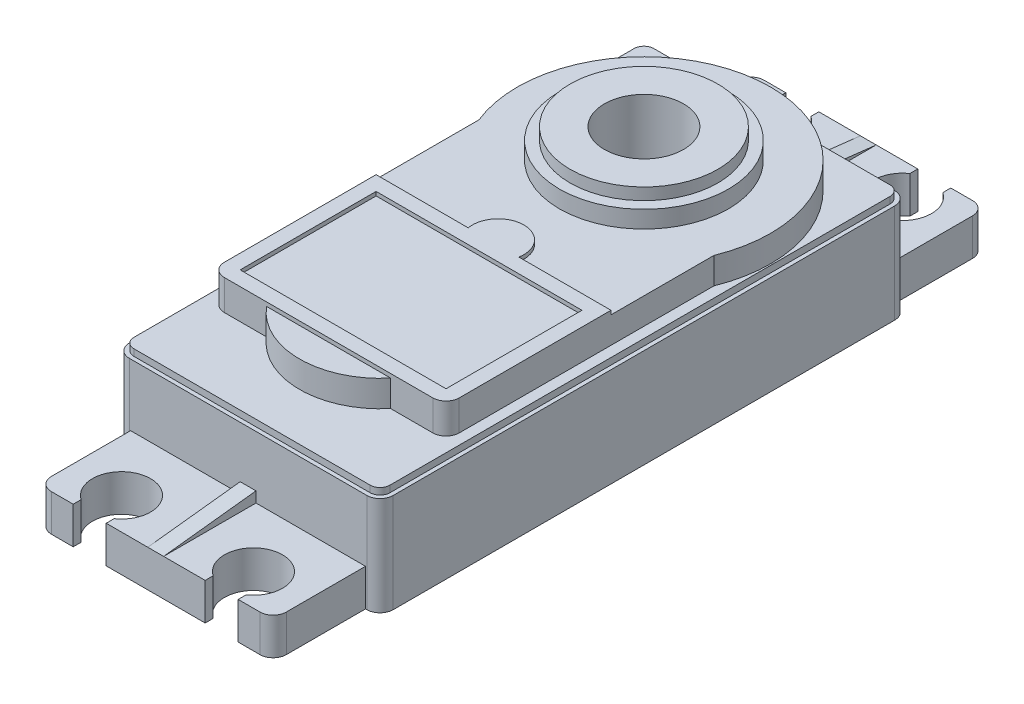
SolidWorks part; units mm, degrees
material "Polyethylene Cross-Linked"
ref_plane "Front Plane" through (0, 0, 0) normal (0, 0, 1) x (1, 0, 0)
ref_plane "Top Plane" through (0, 0, 0) normal (0, 1, 0) x (1, 0, 0)
ref_plane "Right Plane" through (0, 0, 0) normal (1, 0, 0) x (0, 0, -1)
sketch "Sketch6" plane through (0, 0, 0) normal (0, 1, 0) x (1, 0, 0)
  line L0 (-10, 20) -> (10, -20) construction
  line L8 (10, 20) -> (-10, 20)
  line L9 (-10, 20) -> (-10, -20)
  line L10 (-10, -20) -> (10, -20)
  line L11 (10, -20) -> (10, 20)
  dimension "D1" = 40
  dimension "D2" = 20
extrude "Boss-Extrude3" add sketch "Sketch6" along normal blind 8 separate body
sketch "Sketch11" plane through (0, 8, 0) normal (0, 1, 0) x (1, 0, 0)
  line L0 (0, 0) -> (0, 10) construction
  line L1 (0, 10) -> (0, 20) construction
  line L3 (10, 20) -> (-10, 20) construction
  circle A0 centre (0, 10) radius 3
  dimension "D2" = 6
  dimension "D1" = 10
extrude "Cut-Extrude3" cut sketch "Sketch11" against normal up to next
sketch "Sketch12" plane through (0, 0, 20) normal (0, 0, 1) x (1, 0, 0)
  line L1 (-8.9, 2.8) -> (8.9, 2.8)
  line L2 (-8.9, 2.8) -> (-8.9, 0)
  line L3 (-8.9, 0) -> (8.9, 0)
  line L4 (8.9, 2.8) -> (8.9, 0)
  line L6 (-10, 0) -> (10, 0) construction
  dimension "D2" = 2.8
  dimension "D3" = 17.8
extrude "Boss-Extrude4" add sketch "Sketch12" along normal blind 7
sketch "Sketch13" plane through (0, 2.8, 0) normal (0, 1, 0) x (1, 0, 0)
  line L0 (0, -27) -> (0, -20) construction
  line L1 (8.9, -27) -> (-8.9, -27) construction
  line L2 (8.9, -20) -> (-8.9, -20) construction
  line L3 (-6.25, -26.4) -> (-6.25, -27)
  line L4 (-6.25, -27) -> (-3.75, -27)
  line L5 (-3.75, -27) -> (-3.75, -26.4)
  line L6 (-5, -24.5896) -> (-5, -27) construction
  arc A0 (-3.75, -26.4) -> (-6.25, -26.4) centre (-5, -24.5896) ccw
  dimension "D1" = 4.4
  dimension "D2" = 0.6
  dimension "D3" = 5
  dimension "D4" = 2.5
extrude "Cut-Extrude4" cut sketch "Sketch13" against normal through all
mirror "Mirror6" about plane through (0, 0, 0) normal (1, 0, 0) of "Cut-Extrude4"
sketch "Sketch20" plane through (0, 0, 0) normal (0, -1, 0) x (-1, 0, 0)
  line L0 (0, -20) -> (0, -27) construction
  line L1 (-8.9, -20) -> (8.9, -20) construction
  line L3 (3.75, -27) -> (-3.75, -27) construction
  circle A0 centre (0, -25) radius 0.7
  dimension "D1" = 1.4
  dimension "D2" = 5
extrude "Cut-Extrude7" cut sketch "Sketch20" against normal blind 0.5
sketch "Sketch21" plane through (0, 0, 0) normal (1, 0, 0) x (0, 0, -1)
  line L0 (-27, 2.8) -> (-20, 3.6)
  line L1 (-20, 8) -> (-20, 0) construction
  line L2 (-20, 3.6) -> (-20, 2.8)
  line L3 (-20, 2.8) -> (-27, 2.8)
  dimension "D1" = 0.8
extrude "Boss-Extrude8" add sketch "Sketch21" along normal mid plane 1.2
mirror "Mirror7" about plane through (0, 0, 0) normal (0, 0, 1) of "Boss-Extrude8", "Cut-Extrude7", "Mirror6", "Cut-Extrude4", "Boss-Extrude4"
sketch "Sketch28" plane through (0, 8, 0) normal (0, 1, 0) x (1, 0, 0)
  line L0 (-9.7, 19.7) -> (-9.7, -19.7)
  line L1 (-9.7, -19.7) -> (9.7, -19.7)
  line L2 (9.7, -19.7) -> (9.7, 19.7)
  line L3 (9.7, 19.7) -> (-9.7, 19.7)
  line L4 (-10, 20) -> (-10, -20)
  line L5 (-10, -20) -> (10, -20)
  line L6 (10, -20) -> (10, 20)
  line L7 (10, 20) -> (-10, 20)
  line L8 (-10, 20) -> (-10, -20)
  line L9 (-10, -20) -> (10, -20)
  line L10 (10, -20) -> (10, 20)
  line L11 (10, 20) -> (-10, 20)
  dimension "D1" = 0
  dimension "D2" = 0.3
sketch "Sketch16" plane through (0, 8, 0) normal (0, 1, 0) x (1, 0, 0)
  line L0 (-8.9, -13.8986) -> (8.9, -13.8986)
  line L1 (8.9, -13.8986) -> (8.9, 6.4014)
  line L2 (-8.9, -13.8986) -> (-8.9, 6.4014)
  line L3 (0, -13.8986) -> (0, 0) construction
  arc A0 (8.9, 6.4014) -> (-8.9, 6.4014) centre (0, 10) ccw
  circle A1 centre (0, 10) radius 3
  circle A3 centre (0, 10) radius 3 construction
  dimension "D1" = 19.2
  dimension "D3" = 20.3
  dimension "D2" = 17.8
extrude "Boss-Extrude6" add sketch "Sketch16" along normal blind 2
sketch "Sketch23" plane through (0, 8, 0) normal (0, 1, 0) x (1, 0, 0)
  line L1 (-4.7, -13.8986) -> (4.7, -13.8986) construction
  line L2 (-8.9, -13.8986) -> (8.9, -13.8986) construction
  line L3 (0, -13.8986) -> (0, -16.0986) construction
  line L7 (-8.9, -13.8986) -> (8.9, -13.8986)
  line L8 (-8.9, 6.4014) -> (-8.9, -13.8986)
  line L9 (8.9, -13.8986) -> (8.9, 6.4014)
  line L10 (-4.7, -13.8986) -> (4.7, -13.8986)
  arc A0 (-4.7, -13.8986) -> (4.7, -13.8986) centre (0, -9.9782) ccw
  arc A2 (8.9, 6.4014) -> (-8.9, 6.4014) centre (0, 10) ccw
  dimension "D1" = 2.2
  dimension "D2" = 9.4
  dimension "D3" = 0
extrude "Boss-Extrude9" add sketch "Sketch23" along normal up to surface (2 mm away) up to face at (0, 10, 0.449)
sketch "Sketch24" plane through (0, 10, 0) normal (0, 1, 0) x (1, 0, 0)
  circle A0 centre (0, 10) radius 6.4
  circle A1 centre (0, 10) radius 3
  circle A2 centre (0, 10) radius 3 construction
  dimension "D1" = 12.8
extrude "Boss-Extrude10" add sketch "Sketch24" along normal blind 1.3
sketch "Sketch25" plane through (0, 11.3, 0) normal (0, 1, 0) x (1, 0, 0)
  circle A0 centre (0, 10) radius 5.6
  circle A1 centre (0, 10) radius 3
  circle A4 centre (0, 10) radius 3 construction
  dimension "D1" = 11.2
extrude "Boss-Extrude11" add sketch "Sketch25" along normal blind 0.9
sketch "Sketch26" plane through (0, 10, 0) normal (0, 1, 0) x (1, 0, 0)
  line L0 (-8.9, 6.4014) -> (-8.9, -13.8986) construction
  line L1 (-8.9, -1.3986) -> (8.9, -1.3986)
  line L2 (-8.9, -1.3986) -> (-8.9, -13.8986)
  line L3 (-8.9, -13.8986) -> (8.9, -13.8986)
  line L4 (8.9, -1.3986) -> (8.9, -13.8986)
  line L5 (-8.9, -1.3986) -> (8.9, -13.8986) construction
  line L6 (-8.9, -13.8986) -> (8.9, -1.3986) construction
  line L8 (-7.8, -2.4986) -> (7.8, -2.4986)
  line L9 (-7.8, -2.4986) -> (-7.8, -12.7986)
  line L10 (-7.8, -12.7986) -> (7.8, -12.7986)
  line L11 (7.8, -2.4986) -> (7.8, -12.7986)
  line L12 (-7.8, -2.4986) -> (7.8, -12.7986) construction
  line L13 (-7.8, -12.7986) -> (7.8, -2.4986) construction
  point P0 (0, -7.6486)
  point P8 (0, -7.6486)
  dimension "D1" = 12.5
  dimension "D2" = 1.1
  dimension "D3" = 1.1
extrude "Boss-Extrude12" add sketch "Sketch26" along normal blind 0.3
sketch "Sketch27" plane through (0, 10, 0) normal (0, 1, 0) x (1, 0, 0)
  line L0 (7.8, -2.4986) -> (-7.8, -2.4986) construction
  line L1 (1.3038, -2.4986) -> (-1.3038, -2.4986)
  line L2 (0, -2.4986) -> (0, 0) construction
  line L3 (0, 0.9014) -> (0, 0) construction
  arc A0 (1.3038, -2.4986) -> (-1.3038, -2.4986) centre (0, -1.0486) ccw
  dimension "D1" = 3.4
  dimension "D2" = 1.95
extrude "Boss-Extrude13" add sketch "Sketch27" along normal up to surface (0.3 mm away) up to face at (0, 10.3, 7.6486)
extrude "Cut-Extrude8" cut sketch "Sketch28" against normal blind 0.5
fillet "Fillet1" radius 1 10 edges at (-10, 3.75, -20) (10, 3.75, -20) (10, 3.75, 20) (-10, 3.75, 20) (-8.9, 9.15, 13.8986) (8.9, 9.15, 13.8986) (-8.9, 1.4, -27) (8.9, 1.4, -27) (8.9, 1.4, 27) (-8.9, 1.4, 27)
fillet "Fillet2" radius 0.75 4 edges at (-9.7, 7.75, -19.7) (9.7, 7.75, -19.7) (9.7, 7.75, 19.7) (-9.7, 7.75, 19.7)
